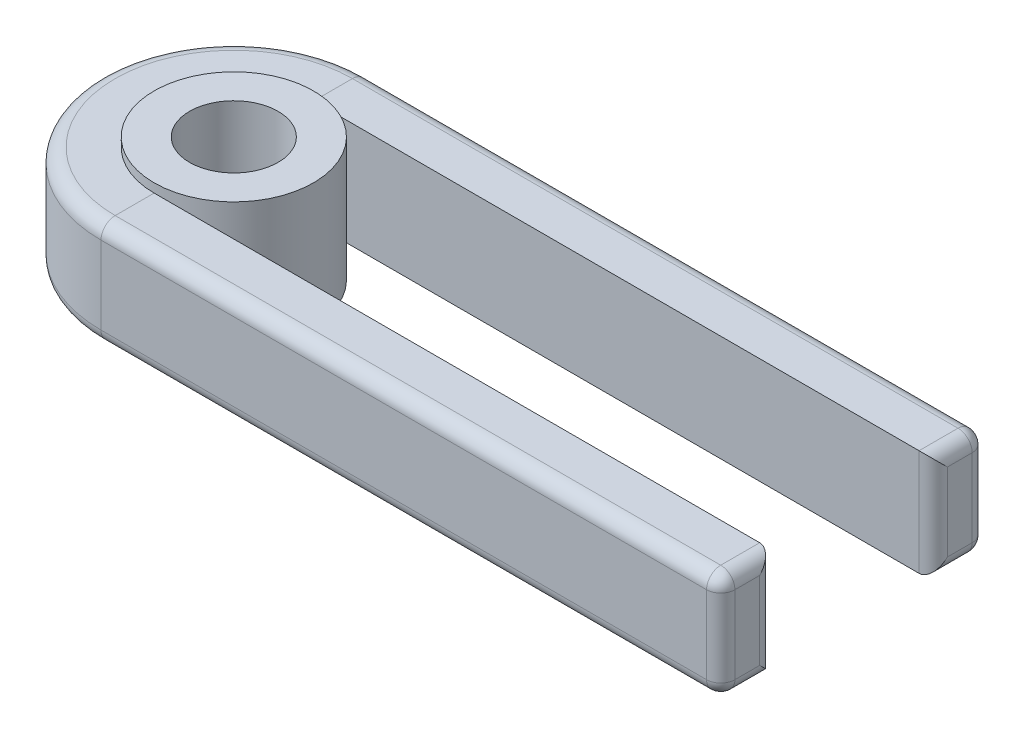
SolidWorks part; units mm, degrees
ref_plane "Front Plane" through (0, 0, 0) normal (0, 0, 1) x (1, 0, 0)
ref_plane "Top Plane" through (0, 0, 0) normal (0, 1, 0) x (1, 0, 0)
ref_plane "Right Plane" through (0, 0, 0) normal (1, 0, 0) x (0, 0, -1)
sketch "Sketch1" plane through (0, 0, 0) normal (0, 1, 0) x (1, 0, 0)
  circle A0 centre (0, 0) radius 4.5
  dimension "D1" = 9
extrude "Boss-Extrude1" add sketch "Sketch1" along normal blind 7
sketch "Sketch2" plane through (0, 7, 0) normal (0, 1, 0) x (1, 0, 0)
  circle A0 centre (0, 0) radius 2.5
  circle A1 centre (0, 0) radius 4.5 construction
  dimension "D1" = 2
extrude "Cut-Extrude1" cut sketch "Sketch2" against normal through all
ref_plane "Plane1" through (0, 3.5, 0) normal (0, 1, 0) x (1, 0, 0)
sketch "Sketch3" plane through (0, 3.5, 0) normal (0, 1, 0) x (1, 0, 0)
  line L0 (0, 6) -> (35, 6)
  line L1 (0, -6) -> (35, -6)
  line L2 (0, 0) -> (0, 6) construction
  line L3 (0, 0) -> (0, -6) construction
  arc A0 (0, 6) -> (0, -6) centre (0, 0) ccw
  dimension "D2" = 6
  dimension "D1" = 35
ref_plane "Plane3" through (0, 0, 0) normal (1, 0, 0) x (0, 0, -1)
ref_plane "Plane4" through (35, 0, 0) normal (1, 0, 0) x (0, 0, -1)
sketch "Sketch4" plane through (35, 0, 0) normal (1, 0, 0) x (0, 0, -1)
  line L1 (4.5, 6.5) -> (7.5, 6.5)
  line L2 (4.5, 6.5) -> (4.5, 0.5)
  line L3 (4.5, 0.5) -> (7.5, 0.5)
  line L4 (7.5, 6.5) -> (7.5, 0.5)
  line L5 (4.5, 6.5) -> (7.5, 0.5) construction
  line L6 (4.5, 0.5) -> (7.5, 6.5) construction
  point P0 (6, 3.5)
  dimension "D1" = 3
  dimension "D2" = 6
sweep "Sweep1" add profiles "Sketch4" path "Sketch3"
fillet "Fillet1" radius 0.8 14 edges at (17.5, 0.5, 7.5) (-7.5, 0.5, 0) (17.5, 6.5, 7.5) (-7.5, 6.5, 0) (35, 6.5, 6) (35, 3.5, 4.5) (35, 0.5, 6) (35, 3.5, 7.5) (35, 0.5, -6) (35, 3.5, -4.5) (35, 6.5, -6) (17.5, 0.5, -7.5) (35, 3.5, -7.5) (17.5, 6.5, -7.5)
